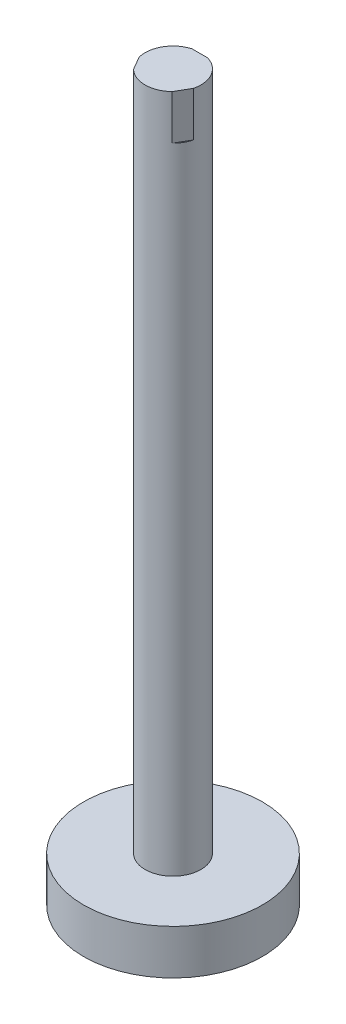
SolidWorks part; units mm, degrees
material "Plain Carbon Steel"
ref_plane "Front Plane" through (0, 0, 0) normal (0, 0, 1) x (1, 0, 0)
ref_plane "Top Plane" through (0, 0, 0) normal (0, 1, 0) x (1, 0, 0)
ref_plane "Right Plane" through (0, 0, 0) normal (1, 0, 0) x (0, 0, -1)
sketch "Sketch1" plane through (0, 0, 0) normal (0, 1, 0) x (1, 0, 0)
  circle A0 centre (0, 0) radius 20
  dimension "D1" = 40
extrude "Boss-Extrude1" add sketch "Sketch1" against normal blind 10
sketch "Sketch2" plane through (0, 0, 0) normal (0, 1, 0) x (1, 0, 0)
  circle A0 centre (0, 0) radius 6.25
  dimension "D1" = 12.5
extrude "Boss-Extrude2" add sketch "Sketch2" along normal blind 152
sketch "Sketch7" plane through (0, 152, 0) normal (0, 1, 0) x (1, 0, 0)
  line L0 (-1.75, 6) -> (1.75, 6)
  circle A0 centre (0, 0) radius 6.25 construction
  arc A1 (1.75, 6) -> (-1.75, 6) centre (0, 0) ccw
  dimension "D1" = 0.25
extrude "Cut-Extrude2" cut sketch "Sketch7" against normal blind 10 contours L0 A1
pattern_circular "CirPattern1" count 3 every 120 about axis through (0, 0, 0) along (0, 1, 0) of "Cut-Extrude2"
sketch "Sketch8" plane through (0, -10, 0) normal (0, -1, 0) x (1, 0, 0)
  circle A0 centre (0, 0) radius 8
  dimension "D1" = 16
extrude "Cut-Extrude3" cut sketch "Sketch8" against normal blind 1
